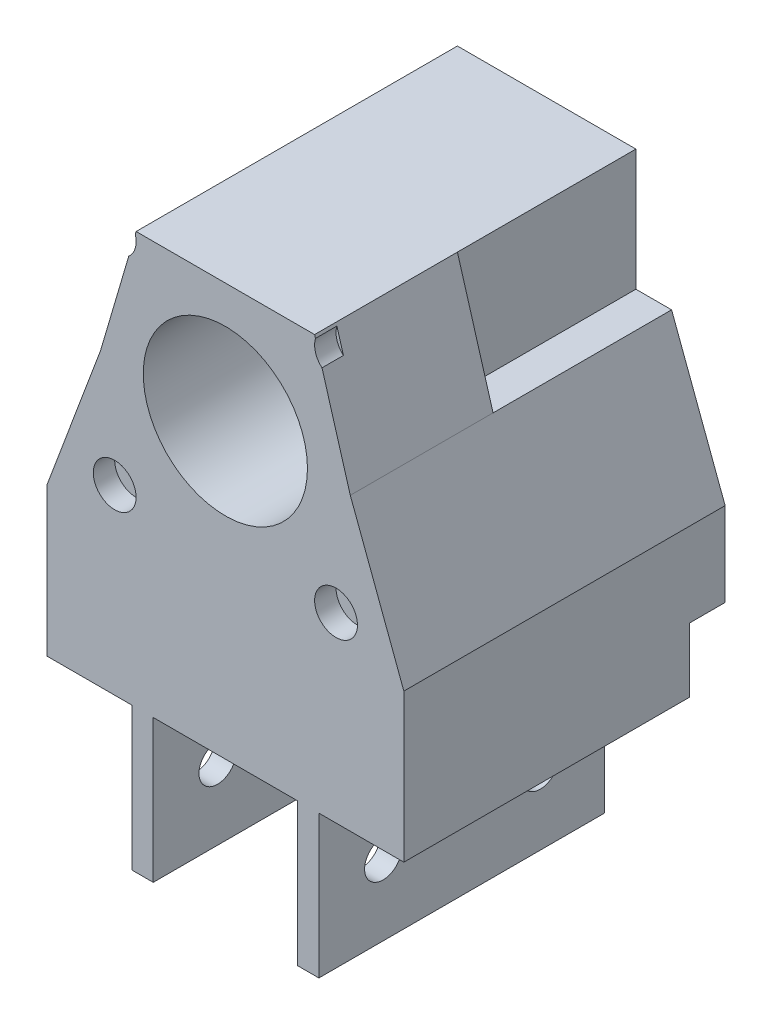
SolidWorks part; units mm, degrees
ref_plane "前视基准面" through (0, 0, 0) normal (0, 0, 1) x (1, 0, 0)
ref_plane "上视基准面" through (0, 0, 0) normal (0, 1, 0) x (1, 0, 0)
ref_plane "右视基准面" through (0, 0, 0) normal (1, 0, 0) x (0, 0, -1)
other "Configuration Table"
sketch "草图1" plane through (0, 0, 0) normal (0, 0, 1) x (1, 0, 0)
  line L0 (0, -39.6057) -> (0, 25.2485) construction
  line L9 (10.1, -25.375) -> (13.1, -25.375)
  line L10 (-25, -5.375) -> (-13.1, -5.375)
  line L11 (-25, -5.375) -> (-25, 5.375)
  line L12 (-25, 5.375) -> (25, 5.375)
  line L13 (25, -5.375) -> (25, 5.375)
  line L14 (-25, -5.375) -> (25, 5.375) construction
  line L15 (-25, 5.375) -> (25, -5.375) construction
  line L16 (-10.1, -5.375) -> (10.1, -5.375)
  line L17 (-13.1, -5.375) -> (-13.1, -25.375)
  line L18 (-13.1, -25.375) -> (-10.1, -25.375)
  line L19 (13.1, -5.375) -> (13.1, -25.375)
  line L21 (-10.1, -25.375) -> (-10.1, -5.375)
  line L22 (-10.1, -5.375) -> (10.1, -5.375)
  line L23 (10.1, -25.375) -> (10.1, -5.375)
  line L24 (-8.4435, -45.2703) -> (10.1, -5.375) construction
  line L25 (-10.1, -5.375) -> (10.5079, -49.7116) construction
  line L26 (-10.1, -5.375) -> (10.1, -5.375)
  line L27 (13.1, -5.375) -> (25, -5.375)
  point P2 (0, 0)
  point P12 (0, -27.1045)
  dimension "D1" = 50
  dimension "D2" = 10.75
  dimension "D3" = 20
  dimension "D4" = 3
  dimension "D5" = 20.2
extrude "凸台-拉伸1" add sketch "草图1" along normal blind 40 contours L19 L27 L13 L12 L11 L10 L17 L18 L21 L16 L23 L9
sketch "草图2" plane through (0, 0, 0) normal (0, 0, -1) x (-1, 0, 0)
  line L0 (0, -5.375) -> (0, 67.3086) construction
  line L1 (10.1, -5.375) -> (-10.1, -5.375) construction
  line L2 (25, 5.375) -> (-25, 5.375) construction
  line L3 (-12.5, 5.375) -> (12.5, 5.375)
  line L4 (-12.5, 5.375) -> (-12.5, 52.375)
  line L5 (-12.5, 52.375) -> (12.5, 52.375)
  line L6 (12.5, 5.375) -> (12.5, 52.375)
  line M14 (25, 5.375) -> (-25, 5.375)
  dimension "D1" = 47
  dimension "D2" = 25
extrude "凸台-拉伸2" add sketch "草图2" against normal up to surface (40 mm away) contours L6 L5 L4 M14 up to face at (0, -10.25, 40)
hole_wizard "孔3" positions "草图9" profile "草图8" legacy end condition through all
sketch "草图9" plane through (0, 0, 40) normal (0, 0, 1) x (1, 0, 0)
  line L0 (0, -5.375) -> (0, 52.375) construction
  line L1 (-10.1, -5.375) -> (10.1, -5.375) construction
  line L2 (12.5, 52.375) -> (-12.5, 52.375) construction
  line L4 (12.5, 5.375) -> (25, 5.375) construction
  point P0 (0, 35.625)
  dimension "D1" = 30.25
sketch "草图8" plane through (0, 35.625, 40) normal (1, 0, 0) x (0, -1, 0)
  line L0 (0, 0) -> (0, 40)
  line L1 (0, 40) -> (11.5, 40)
  line L2 (11.5, 40) -> (11.5, 0)
  line L3 (11.5, 0) -> (0, 0)
  line L4 (0, 110) -> (0, -10) construction
  dimension "直径" = 23
  dimension "深度" = 40
sketch "草图10" plane through (0, 0, 40) normal (0, 0, 1) x (1, 0, 0)
  line L0 (12.5, 35.375) -> (17.5, 35.375)
  line L1 (12.5, 5.375) -> (12.5, 52.375) construction
  line L2 (17.5, 35.375) -> (25, 15.375)
  line L3 (25, 15.375) -> (25, 5.375)
  line L4 (12.5, 35.375) -> (12.5, 5.375)
  line L5 (12.5, 5.375) -> (25, 5.375)
  line L6 (0, 52.375) -> (0, -5.375) construction
  line L7 (12.5, 52.375) -> (-12.5, 52.375) construction
  line L8 (-10.1, -5.375) -> (10.1, -5.375) construction
  line L9 (-12.5, 35.375) -> (-12.5, 5.375)
  line L10 (-12.5, 35.375) -> (-17.5, 35.375)
  line L11 (-17.5, 35.375) -> (-25, 15.375)
  line L12 (-25, 15.375) -> (-25, 5.375)
  line L13 (-12.5, 5.375) -> (-25, 5.375)
  dimension "D1" = 30
  dimension "D2" = 5
  dimension "D3" = 10
extrude "凸台-拉伸3" add sketch "草图10" against normal up to surface (40 mm away) up to face at (11.5, 35.625, 0)
sketch "草图12" plane through (0, 0, 40) normal (0, 0, 1) x (1, 0, 0)
  line L0 (12.5, 52.375) -> (17.5, 35.375)
  line L1 (25, 15.375) -> (17.5, 35.375) construction
  line L2 (17.5, 35.375) -> (12.5, 35.375)
  line L3 (12.5, 35.375) -> (12.5, 52.375)
  line L4 (-12.5, 52.375) -> (-17.5, 35.375)
  line L5 (-17.5, 35.375) -> (-12.5, 35.375)
  line L6 (-12.5, 35.375) -> (-12.5, 52.375)
extrude "凸台-拉伸5" add sketch "草图12" against normal blind 20
hole_wizard "孔4" positions "草图13" profile "草图14" legacy end condition through all
sketch "草图13" plane through (13.1, 0, 0) normal (1, 0, 0) x (0, 0, -1)
  line L0 (-40, -5.375) -> (0, -5.375) construction
  line L4 (0, -5.375) -> (0, -25.375) construction
  line L5 (-40, -5.375) -> (-40, -25.375) construction
  point P0 (-31, -15.375)
  point P2 (-9, -15.375)
  dimension "D1" = 10
  dimension "D2" = 10
  dimension "D3" = 9
  dimension "D4" = 9
sketch "草图14" plane through (13.1, -15.375, 31) normal (0, 1, 0) x (0, 0, -1)
  line L0 (0, 0) -> (0, 38.1)
  line L1 (0, 38.1) -> (2.6, 38.1)
  line L2 (2.6, 38.1) -> (2.6, 0)
  line L3 (2.6, 0) -> (0, 0)
  line L4 (0, 110) -> (0, -10) construction
  dimension "直径" = 5.2
  dimension "深度" = 38.1
sketch "草图15" plane through (0, 0, 40) normal (0, 0, 1) x (1, 0, 0)
  circle A0 centre (-15.5, 51.125) radius 3
  circle A1 centre (15.5, 51.125) radius 3
  circle A2 centre (-15.5, 20.125) radius 3
  circle A3 centre (15.5, 20.125) radius 3
  dimension "D1" = 6
  dimension "D2" = 6
  dimension "D3" = 6
  dimension "D4" = 6
extrude "切除-拉伸1" cut sketch "草图15" against normal blind 3
sketch "草图16" plane through (0, 0, 0) normal (0, 0, -1) x (-1, 0, 0)
  line L0 (-25, 3.625) -> (25, 3.625)
  line L1 (-25, -5.375) -> (-25, 15.375) construction
  line L2 (25, -5.375) -> (25, 15.375) construction
  line L3 (-13.1, -5.375) -> (-25, -5.375) construction
  line L4 (25, 3.625) -> (25, 15.375)
  line L5 (25, 15.375) -> (17.5, 35.375)
  line L6 (17.5, 35.375) -> (12.5, 35.375)
  line L7 (12.5, 35.375) -> (12.5, 52.375)
  line L8 (12.5, 52.375) -> (-12.5, 52.375)
  line L9 (-12.5, 52.375) -> (-12.5, 35.375)
  line L10 (-12.5, 35.375) -> (-17.5, 35.375)
  line L11 (-17.5, 35.375) -> (-25, 15.375)
  line L12 (-25, 15.375) -> (-25, 3.625)
  circle A0 centre (0, 35.625) radius 11.5
  dimension "D1" = 9
extrude "凸台-拉伸6" add sketch "草图16" along normal blind 5
